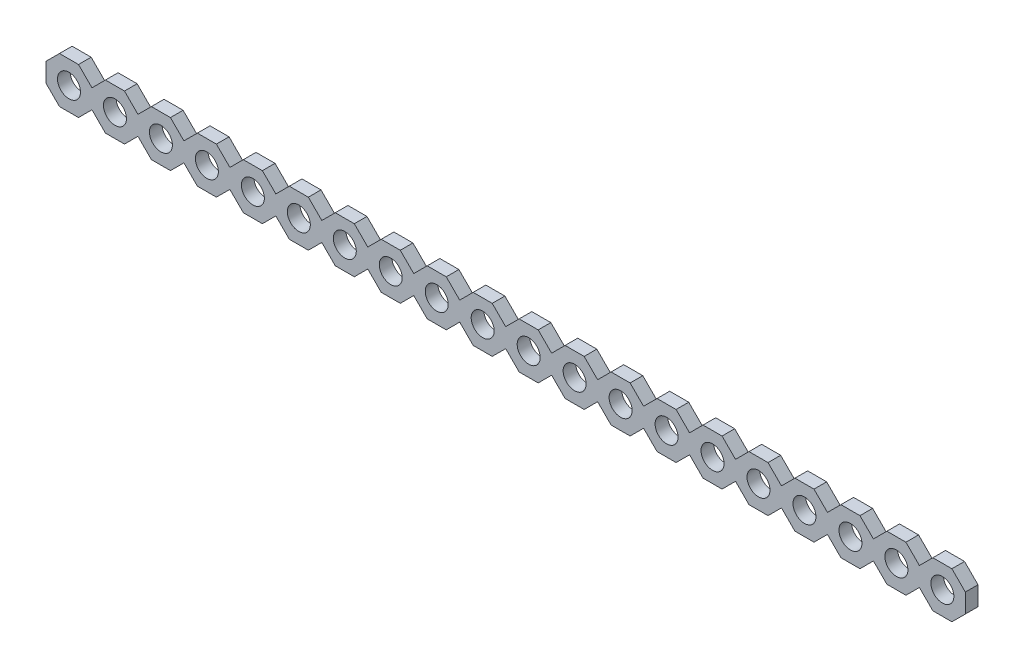
SolidWorks part; units mm, degrees
material "Alliage 6061"
ref_plane "Face" through (0, 0, 0) normal (0, 0, 1) x (1, 0, 0)
ref_plane "Dessus" through (0, 0, 0) normal (0, 1, 0) x (1, 0, 0)
ref_plane "Droite" through (0, 0, 0) normal (1, 0, 0) x (0, 0, -1)
sketch "Esquisse1" plane through (0, 0, 0) normal (0, 0, 1) x (1, 0, 0)
  line L1 (-1.6569, -4) -> (1.6569, -4)
  line L2 (1.6569, -4) -> (4, -1.6569)
  line L3 (4, -1.6569) -> (4, 1.6569)
  line L4 (4, 1.6569) -> (1.6569, 4)
  line L5 (1.6569, 4) -> (-1.6569, 4)
  line L6 (-1.6569, 4) -> (-4, 1.6569)
  line L7 (-4, 1.6569) -> (-4, -1.6569)
  line L8 (-4, -1.6569) -> (-1.6569, -4)
  circle A0 centre (0, 0) radius 2
  circle A1 centre (0, 0) radius 4 construction
  dimension "D1" = 4
  dimension "D2" = 8
extrude "Boss.-Extru.1" add sketch "Esquisse1" along normal blind 2.2
pattern_linear "Répétition linéaire1" count 20 spacing 8 along (1, 0, 0) of "Boss.-Extru.1"
